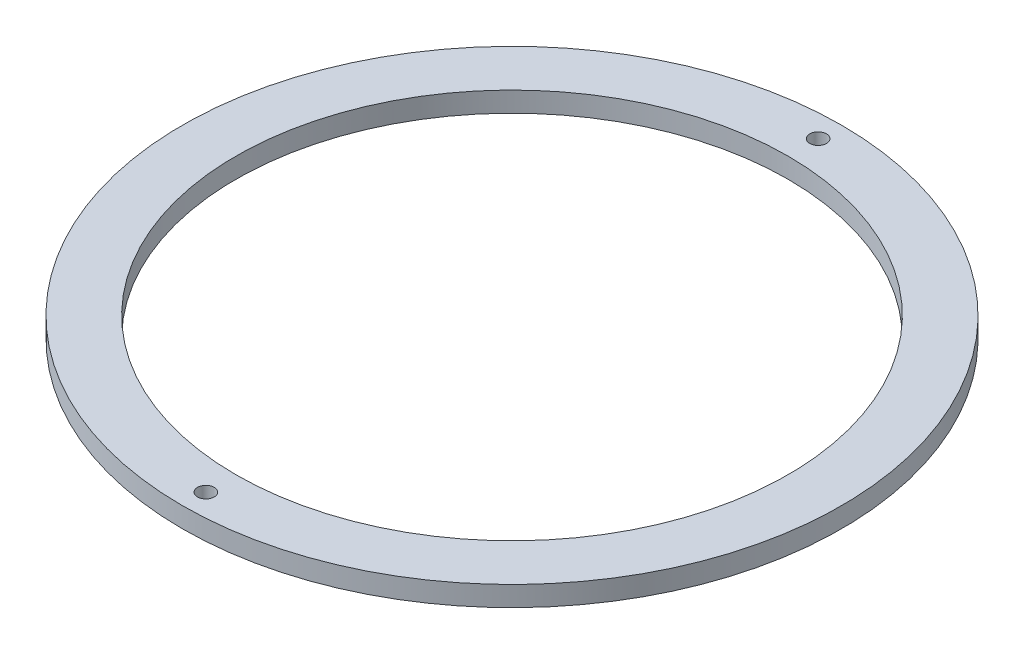
SolidWorks part; units mm, degrees
ref_plane "Front Plane" through (0, 0, 0) normal (0, 0, 1) x (1, 0, 0)
ref_plane "Top Plane" through (0, 0, 0) normal (0, 1, 0) x (1, 0, 0)
ref_plane "Right Plane" through (0, 0, 0) normal (1, 0, 0) x (0, 0, -1)
sketch "Sketch1" plane through (0, 0, 0) normal (0, 1, 0) x (1, 0, 0)
  circle A0 centre (0, 0) radius 41.25
  circle A1 centre (0, 0) radius 49.25
  circle A2 centre (0, 0) radius 42.75 construction
  circle A3 centre (0, 0) radius 42.75 construction
  dimension "D1" = 1.5
  dimension "D2" = 8
extrude "Boss-Extrude1" add sketch "Sketch1" along normal blind 3
sketch "Sketch2" [suppressed] plane through (0, 0, 0) normal (0, 1, 0) x (1, 0, 0)
  circle A0 centre (0, 0) radius 21.5
  circle A1 centre (0, 0) radius 31.5
  circle A2 centre (0, 0) radius 23.5 construction
  circle A3 centre (0, 0) radius 23.5 construction
  dimension "D1" = 2
  dimension "D2" = 10
extrude "Boss-Extrude2" [suppressed] add sketch "Sketch2" along normal blind 3
sketch "Sketch3" [suppressed] plane through (0, 3, 0) normal (0, 1, 0) x (1, 0, 0)
  circle A0 centre (0, -26.5) radius 1.25 construction
  circle A1 centre (0, 26.5) radius 1.25 construction
  circle A2 centre (0, -26.5) radius 1.25 construction
  circle A3 centre (0, 26.5) radius 1.25 construction
  circle A4 centre (0, -26.5) radius 1.6
  circle A5 centre (0, 26.5) radius 1.6
  dimension "D1" = 3.2
extrude "Cut-Extrude1" [suppressed] cut sketch "Sketch3" against normal through all
sketch "Sketch4" plane through (0, 3, 0) normal (0, 1, 0) x (1, 0, 0)
  circle A0 centre (0, 45.75) radius 1.25 construction
  circle A1 centre (0, -45.75) radius 1.25 construction
  circle A2 centre (0, 45.75) radius 1.25
  circle A3 centre (0, -45.75) radius 1.25
extrude "Cut-Extrude2" cut sketch "Sketch4" against normal through all
